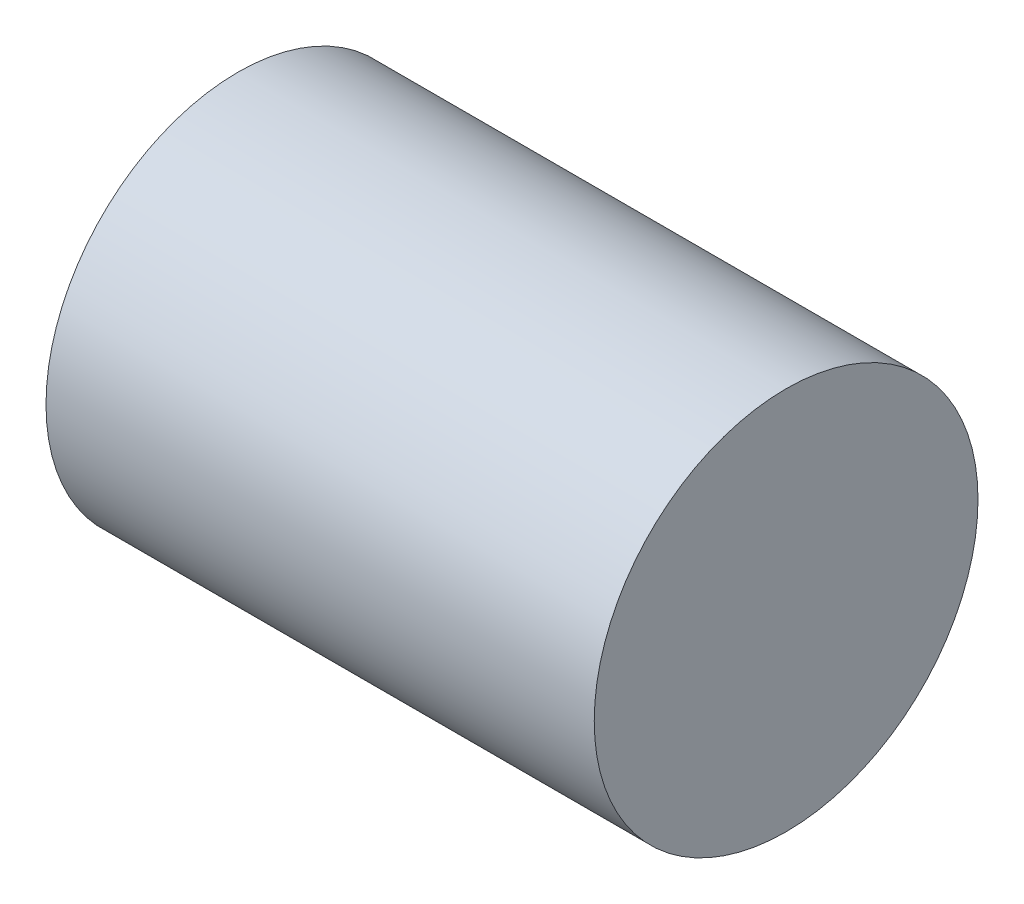
SolidWorks part; units mm, degrees
ref_plane "Front Plane" through (0, 0, 0) normal (0, 0, 1) x (1, 0, 0)
ref_plane "Top Plane" through (0, 0, 0) normal (0, 1, 0) x (1, 0, 0)
ref_plane "Right Plane" through (0, 0, 0) normal (1, 0, 0) x (0, 0, -1)
sketch "Sketch1" plane through (0, 0, 0) normal (1, 0, 0) x (0, 0, -1)
  circle A0 centre (0, 0) radius 14
  dimension "D1" = 28
extrude "Boss-Extrude1" add sketch "Sketch1" along normal blind 40
sketch "Sketch2" plane through (0, 0, 0) normal (-1, 0, 0) x (0, 0, 1)
  circle A0 centre (0, 0) radius 1.15
  dimension "D1" = 2.3
extrude "Boss-Extrude2" add sketch "Sketch2" along normal blind 6.5
